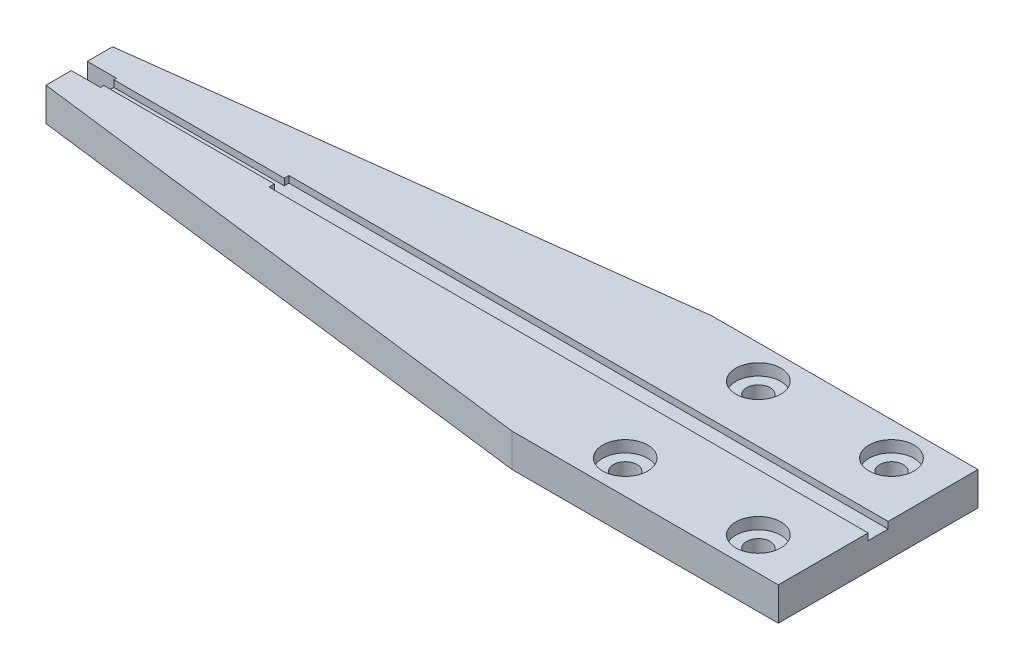
SolidWorks part; units mm, degrees
ref_plane "Front Plane" through (0, 0, 0) normal (0, 0, 1) x (1, 0, 0)
ref_plane "Top Plane" through (0, 0, 0) normal (0, 1, 0) x (1, 0, 0)
ref_plane "Right Plane" through (0, 0, 0) normal (1, 0, 0) x (0, 0, -1)
sketch "Sketch2" plane through (0, 0, 0) normal (1, 0, 0) x (0, 0, -1)
  line L1 (-19.05, 3.175) -> (19.05, 3.175)
  line L2 (-19.05, 3.175) -> (-19.05, -3.175)
  line L3 (-19.05, -3.175) -> (19.05, -3.175)
  line L4 (19.05, 3.175) -> (19.05, -3.175)
  dimension "D1" = 38.1
  dimension "D2" = 6.35
  dimension "D3" = 3.175
  dimension "D4" = 19.05
extrude "Boss-Extrude1" add sketch "Sketch2" along normal blind 152.4
hole_wizard "CBORE for M4 SBHCS1" positions "Sketch5" profile "Sketch6" counterbore size "M4" standard "ANSI Metric" end condition through all
sketch "Sketch5" plane through (0, 3.175, 0) normal (0, 1, 0) x (1, 0, 0)
  line L0 (152.4, 19.05) -> (0, 19.05) construction
  line L1 (152.4, -19.05) -> (0, -19.05) construction
  point P0 (142.2476, -12.7)
  point P2 (142.2476, 12.7)
  point P9 (116.8476, 12.7)
  point P11 (116.8476, -12.7)
  dimension "D1" = 25.4
  dimension "D2" = 6.35
  dimension "D3" = 6.35
  dimension "D4" = 25.4
  dimension "D5" = 25.4
  dimension "D6" = 6.35
  dimension "D7" = 6.35
sketch "Sketch6" plane through (142.2476, 3.175, 12.7) normal (1, 0, 0) x (0, 0, 1)
  line L0 (0, 0) -> (0, 6.35)
  line L1 (0, 6.35) -> (2.25, 6.35)
  line L3 (2.25, 6.35) -> (2.25, 2.2)
  line L4 (2.25, 2.2) -> (4.3, 2.2)
  line L5 (4.3, 2.2) -> (4.3, 0)
  line L7 (4.3, 0) -> (0, 0)
  line L11 (0, -6.35) -> (0, 107.95) construction
  dimension "Thru Hole Dia." = 4.5
  dimension "Thru Hole Depth" = 6.35
  dimension "C'Bore Dia." = 8.6
  dimension "C'Bore Depth" = 2.2
sketch "Sketch9" plane through (0, 0, 0) normal (-1, 0, 0) x (0, 0, 1)
  line L0 (-1.524, 3.175) -> (-1.524, 0.127)
  line L1 (-19.05, 3.175) -> (19.05, 3.175) construction
  line L2 (-1.524, 0.127) -> (1.524, 0.127)
  line L3 (1.524, 0.127) -> (1.524, 3.175)
  line L4 (1.524, 3.175) -> (-1.524, 3.175)
  dimension "D1" = 3.048
  dimension "D2" = 1.524
  dimension "D3" = 3.048
extrude "Cut-Extrude1" cut sketch "Sketch9" against normal blind 5.588
sketch "Sketch12" plane through (0, 3.175, 0) normal (0, 1, 0) x (1, 0, 0)
  line L0 (38.1, 1.905) -> (152.4, 1.905)
  line L1 (152.4, 1.905) -> (152.4, -1.905)
  line L2 (152.4, -1.905) -> (38.1, -1.905)
  line L3 (38.1, -1.905) -> (38.1, 1.905)
  line L6 (0, 0) -> (38.1, 0) construction
  point P7 (38.1, 0)
  dimension "D1" = 1.905
  dimension "D2" = 114.3
  dimension "D3" = 38.1
extrude "Cut-Extrude2" cut sketch "Sketch12" against normal blind 1.27
sketch "Sketch13" plane through (0, 3.175, 0) normal (0, 1, 0) x (1, 0, 0)
  line L0 (5.588, 1.016) -> (38.1, 1.016)
  line L1 (5.588, -1.524) -> (5.588, 1.524) construction
  line L2 (38.1, 1.905) -> (38.1, -1.905) construction
  line L3 (38.1, 1.016) -> (38.1, -0.889)
  line L4 (38.1, -0.889) -> (5.588, -0.889)
  line L5 (5.588, 1.524) -> (5.588, -1.524) construction
  line L6 (5.588, -0.889) -> (5.588, 1.016)
  line L7 (0, 0) -> (152.4, 0) construction
  line L8 (152.4, -1.905) -> (152.4, 1.905) construction
  dimension "D1" = 1.905
  dimension "D2" = 1.016
extrude "Cut-Extrude3" cut sketch "Sketch13" against normal blind 1.27
sketch "Sketch14" plane through (0, 3.175, 0) normal (0, 1, 0) x (1, 0, 0)
  line L5 (0, 6.35) -> (0, 19.05)
  line L6 (0, 19.05) -> (0, 1.524) construction
  line L7 (0, 19.05) -> (101.6, 19.05)
  line L8 (152.4, 19.05) -> (0, 19.05) construction
  line L9 (0, 6.35) -> (101.6, 19.05)
  dimension "D1" = 101.6
  dimension "D2" = 12.7
extrude "Cut-Extrude4" cut sketch "Sketch14" against normal blind 6.35
sketch "Sketch15" plane through (0, 3.175, 0) normal (0, 1, 0) x (1, 0, 0)
  line L0 (0, -6.35) -> (101.6, -19.05)
  line L1 (0, -1.524) -> (0, -19.05) construction
  line L2 (152.4, -19.05) -> (0, -19.05) construction
  line L3 (101.6, -19.05) -> (0, -19.05)
  line L4 (0, -19.05) -> (0, -6.35)
  dimension "D1" = 101.6
  dimension "D2" = 12.7
extrude "Cut-Extrude5" cut sketch "Sketch15" against normal blind 6.35
